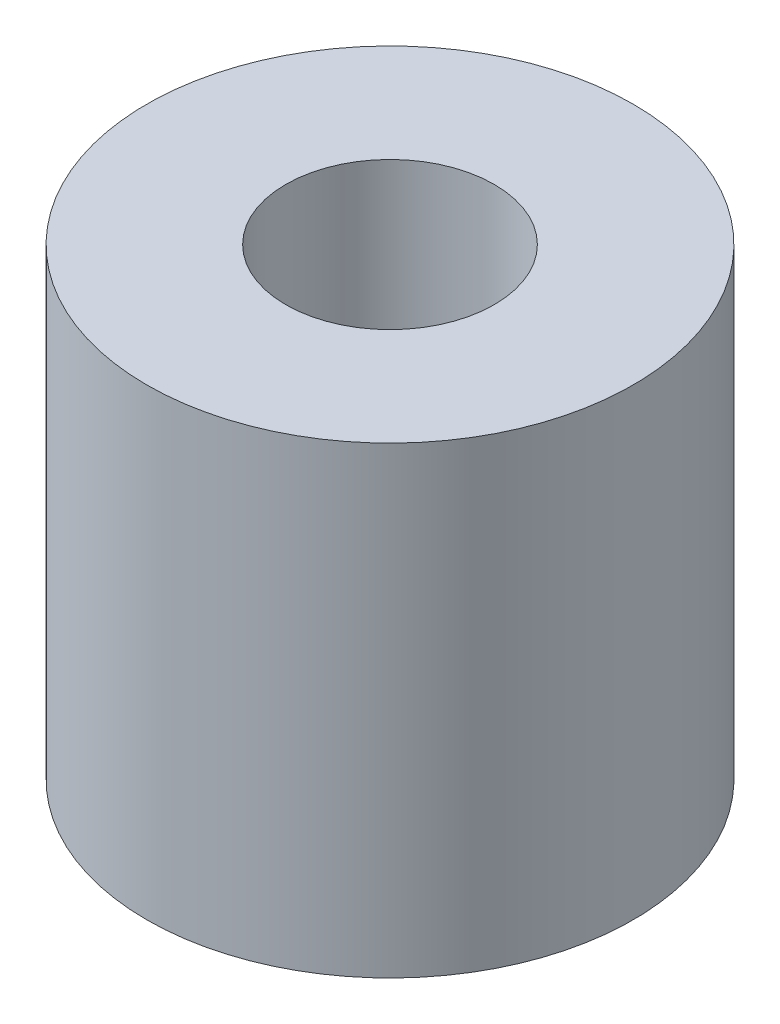
SolidWorks part; units mm, degrees
ref_plane "Front Plane" through (0, 0, 0) normal (0, 0, 1) x (1, 0, 0)
ref_plane "Top Plane" through (0, 0, 0) normal (0, 1, 0) x (1, 0, 0)
ref_plane "Right Plane" through (0, 0, 0) normal (1, 0, 0) x (0, 0, -1)
sketch "Sketch1" plane through (0, 0, 0) normal (0, 1, 0) x (1, 0, 0)
  circle A0 centre (0, 0) radius 9
  circle A1 centre (0, 0) radius 21
  point P4 (0, 0)
  dimension "D1" = 42
  dimension "D2" = 18
extrude "Boss-Extrude1" add sketch "Sketch1" along normal blind 40
